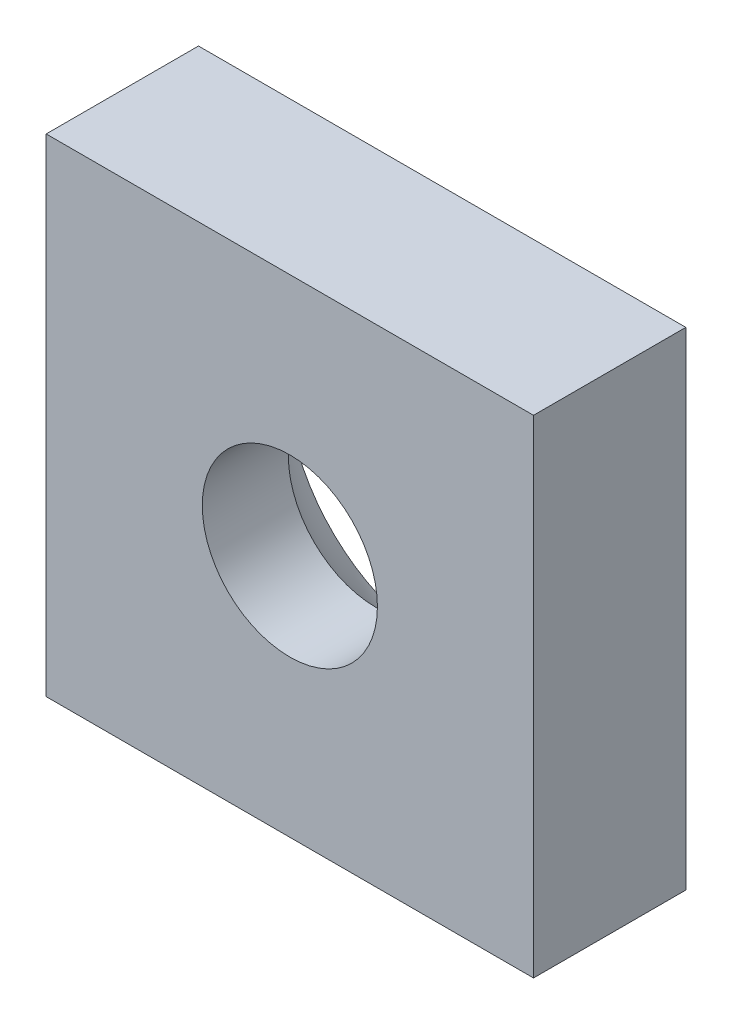
SolidWorks part; units mm, degrees
ref_plane "front" through (0, 0, 0) normal (0, 0, 1) x (1, 0, 0)
ref_plane "top" through (0, 0, 0) normal (0, 1, 0) x (1, 0, 0)
ref_plane "right" through (0, 0, 0) normal (1, 0, 0) x (0, 0, -1)
sketch "Sketch2" plane through (0, 0, 0) normal (1, 0, 0) x (0, 0, -1)
  line L0 (0, 0) -> (19.2914, 0) construction
  line L1 (-34.0616, 0) -> (0, 0)
  line L2 (0, 0) -> (0, 18.796)
  line L3 (-9.525, -25.4) -> (-9.525, 25.4)
  line L4 (-9.525, 25.4) -> (-25.4, 25.4)
  line L5 (-25.4, 25.4) -> (-25.4, -25.4)
  line L6 (-25.4, -25.4) -> (-9.525, -25.4)
  line L7 (-16.4307, 9.1281) -> (-34.0616, 9.1281)
  line L8 (-34.0616, 9.1281) -> (-34.0616, 0)
  line L9 (-33.1112, 9.4034) -> (12.3111, 7.4203)
  arc A0 (0, 18.796) -> (-16.4307, 9.1281) centre (0, 0) ccw
  point P10 (-25.4, 0)
  dimension "D1" = 18.796
  dimension "D2" = 9.525
  dimension "D3" = 15.875
  dimension "D4" = 50.8
  dimension "D5" = 18.2562
  dimension "D6" = 7.9502
  dimension "D7" = 2.5
sketch "Sketch3" plane through (0, 0, 0) normal (1, 0, 0) x (0, 0, -1)
  line L4 (-9.525, -25.4) -> (-9.525, 25.4)
  line L5 (-9.525, 25.4) -> (-25.4, 25.4)
  line L6 (-25.4, 25.4) -> (-25.4, -25.4)
  line L7 (-25.4, -25.4) -> (-9.525, -25.4)
  line L8 (-9.525, -25.4) -> (-9.525, 25.4)
  line L9 (-9.525, 25.4) -> (-25.4, 25.4)
  line L10 (-25.4, 25.4) -> (-25.4, -25.4)
  line L11 (-25.4, -25.4) -> (-9.525, -25.4)
  dimension "D1" = 0
extrude "Extrude2" add sketch "Sketch3" along normal mid plane 50.8
sketch "Sketch4" plane through (0, 0, 0) normal (1, 0, 0) x (0, 0, -1)
  line L0 (0, 0) -> (19.2914, 0) construction
  line L1 (0, 0) -> (19.2914, 0) construction
  line L2 (-34.0616, 0) -> (0, 0)
  line L3 (0, 0) -> (0, 18.796)
  line L4 (-34.0616, 0) -> (0, 0)
  line L5 (0, 0) -> (0, 18.796)
  line L10 (-34.0616, 9.1281) -> (-34.0616, 0)
  line L11 (-34.0616, 9.1281) -> (-34.0616, 0)
  line L12 (-16.4307, 9.1281) -> (-34.0616, 9.1281)
  line L13 (-16.4307, 9.1281) -> (-34.0616, 9.1281)
  arc A1 (0, 18.796) -> (-16.4307, 9.1281) centre (0, 0) ccw
  arc A2 (0, 18.796) -> (-16.4307, 9.1281) centre (0, 0) ccw
  dimension "D1" = 0
revolve "Cut-Revolve2" cut sketch "Sketch4" angle 360 about L1
